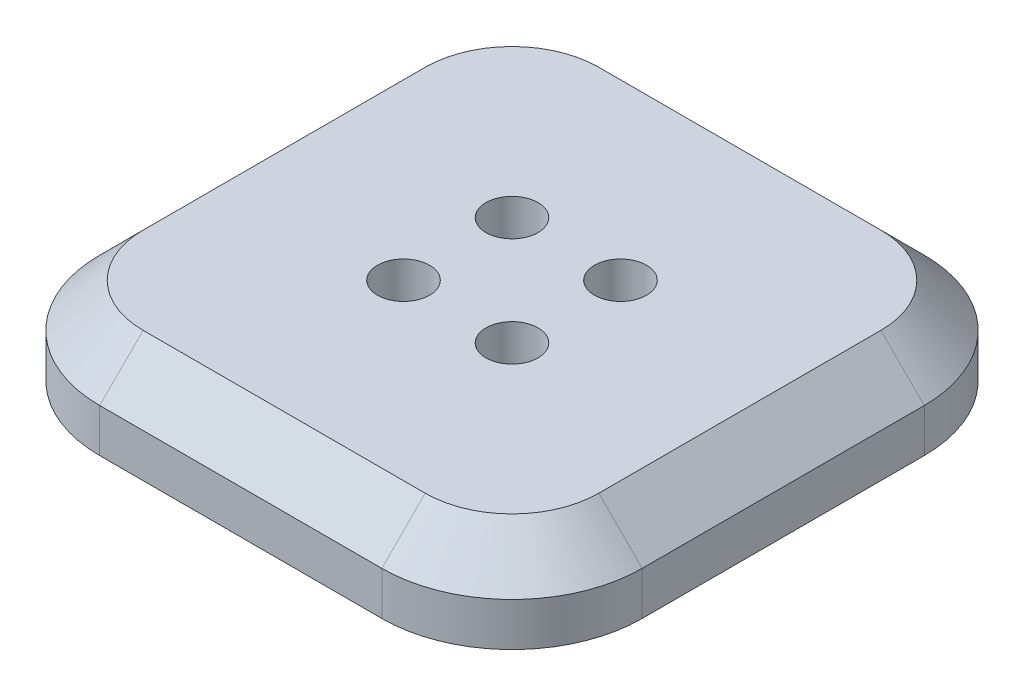
SolidWorks part; units mm, degrees
ref_plane "前基準面" through (0, 0, 0) normal (0, 0, 1) x (1, 0, 0)
ref_plane "上基準面" through (0, 0, 0) normal (0, 1, 0) x (1, 0, 0)
ref_plane "右基準面" through (0, 0, 0) normal (1, 0, 0) x (0, 0, -1)
sketch "草圖1" plane through (0, 0, 0) normal (0, 1, 0) x (1, 0, 0)
  line L1 (0, 0) -> (125, 0)
  line L2 (0, 0) -> (0, 125)
  line L3 (0, 125) -> (125, 125)
  line L4 (125, 0) -> (125, 125)
  dimension "D1" = 125
  dimension "D2" = 125
extrude "填料-伸長1" add sketch "草圖1" along normal blind 20
fillet "圓角1" radius 30 4 edges at (0, 10, -125) (125, 10, -125) (125, 10, 0) (0, 10, 0)
chamfer "導角1" distance 10 angle 45 8 edges at (0, 20, -62.5) (8.7868, 20, -8.7868) (8.7868, 20, -116.2132) (62.5, 20, 0) (62.5, 20, -125) (116.2132, 20, -8.7868) (116.2132, 20, -116.2132) (125, 20, -62.5)
sketch "草圖2" plane through (0, 0, 0) normal (0, -1, 0) x (1, 0, 0)
  line L0 (30, 0) -> (95, 0) construction
  line L1 (25, -25) -> (100, -25)
  line L2 (25, -25) -> (25, -100)
  line L3 (25, -100) -> (100, -100)
  line L4 (100, -25) -> (100, -100)
  line L5 (95, -125) -> (30, -125) construction
  line L6 (125, -30) -> (125, -95) construction
  line L7 (0, -95) -> (0, -30) construction
  dimension "D1" = 25
  dimension "D2" = 25
  dimension "D3" = 25
  dimension "D4" = 25
sketch "草圖4" plane through (0, 20, 0) normal (0, 1, 0) x (1, 0, 0)
  line L0 (25, 25) -> (25, 100) construction
  line L1 (50, 50) -> (75, 50)
  line L2 (50, 50) -> (50, 75)
  line L3 (50, 75) -> (75, 75)
  line L4 (75, 50) -> (75, 75)
  line L5 (25, 25) -> (100, 25) construction
  line L6 (100, 25) -> (100, 100) construction
  line L7 (25, 100) -> (100, 100) construction
  dimension "D1" = 25
  dimension "D2" = 25
  dimension "D3" = 25
  dimension "D4" = 25
hole_wizard "Ø20.0mm 定位孔1" positions "3D草圖2" profile "草圖6" hole size "Ø20.0" standard "ISO"
sketch3d "3D草圖2"
  point P0 (50, 20, -50)
  point P3 (50, 20, -75)
  point P6 (75, 20, -75)
  point P9 (75, 20, -50)
  point P12 (25, 0, -25)
  point P15 (100, 0, -25)
  point P18 (100, 0, -100)
  point P25 (25, 0, -100)
sketch "草圖6" plane through (50, 20, -50) normal (1, 0, 0) x (0, 0, 1)
  line L0 (0, 0) -> (0, 13.6052)
  line L1 (0, 13.6052) -> (6, 10)
  line L2 (6, 10) -> (6, 0)
  line L5 (6, 0) -> (0, 0)
  line L10 (0, 13.6052) -> (-6, 10) construction
  line L11 (0, -6.35) -> (0, 107.95) construction
  dimension "鑽孔直徑" = 12
  dimension "鑽孔深度" = 10
  dimension "導頭角度" = 118
